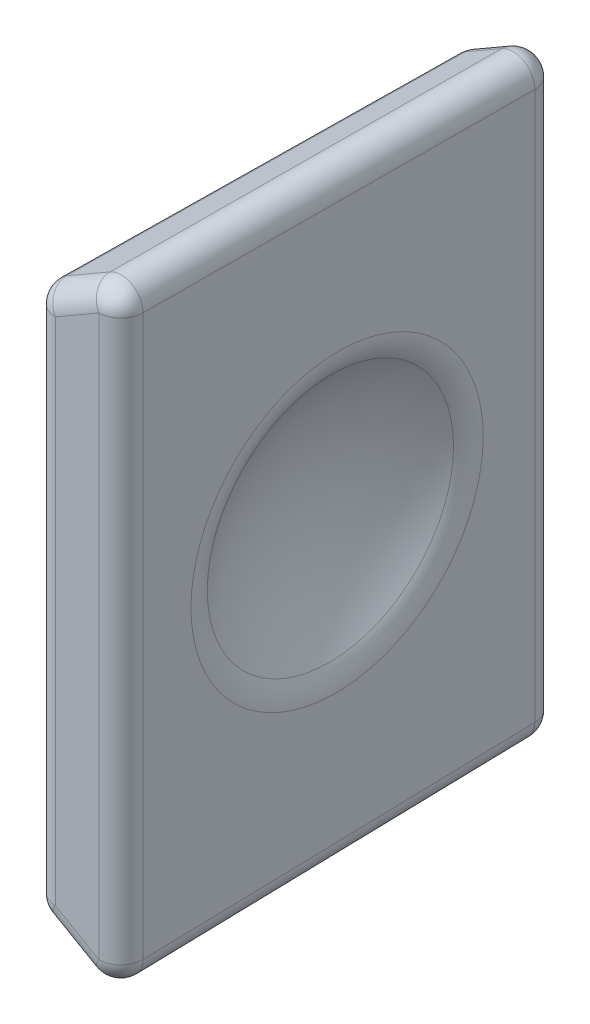
SolidWorks part; units mm, degrees
ref_plane "Front Plane" through (0, 0, 0) normal (0, 0, 1) x (1, 0, 0)
ref_plane "Top Plane" through (0, 0, 0) normal (0, 1, 0) x (1, 0, 0)
ref_plane "Right Plane" through (0, 0, 0) normal (1, 0, 0) x (0, 0, -1)
sketch "Sketch1" plane through (0, 0, 0) normal (0, 0, 1) x (1, 0, 0)
  line L0 (-4, 12.1906) -> (-4, -12.1906)
  line L1 (-4, 12.1906) -> (0, 14.5)
  line L2 (0, 14.5) -> (0, -14.5)
  line L15 (0, -14.5) -> (-4, -12.1906)
  line L50 (0, -14.5) -> (0, -5.2931) construction
  line L53 (0, 1.4892) -> (0, 14.5) construction
  dimension "D2" = 60
  dimension "D1" = 60
  dimension "D3" = 29
  dimension "D4" = 4
extrude "Boss-Extrude1" add sketch "Sketch1" against normal blind 20 draft 0.5
fillet "Fillet1" radius 1 12 edges at (-0.0873, 14.3488, -10) (-0.0873, -14.3488, -10) (-3.9127, -12.1402, -10) (-3.9127, 12.1402, -10) (-3.8255, 0, -20) (-0.1745, 0, -20) (-2, -13.1438, -20) (-4, 0, 0) (0, 0, 0) (-2, -13.3453, 0) (-2, 13.1438, -20) (-2, 13.3453, 0)
sketch "Sketch2" plane through (0, 0, 0) normal (0, 1, 0) x (1, 0, 0)
  line L0 (0, 0) -> (0, 10.0007)
  line L1 (0, 10.0007) -> (8.7268, 10.0007)
  line L2 (8.7268, 20.7276) -> (8.7268, -0.7261)
  line L3 (-0.6702, 20) -> (-0.1702, 20)
  line L4 (-0.1702, 20) -> (0, 10.0007)
  circle A0 centre (8.7268, 10.0007) radius 10.7268
  arc A1 (-0.1702, 19.5044) -> (-0.6702, 20) centre (-0.6702, 19.5) ccw construction
  arc A2 (-0.1702, 19.5044) -> (-0.6702, 20) centre (-0.6702, 19.5) ccw construction
  point P5 (-2, 10.0007)
  dimension "D1" = 2
revolve "Cut-Revolve1" cut sketch "Sketch2" angle 360 about L2
fillet "Fillet2" radius 2 1 edges at (-0.14, 0, -16.0377)
